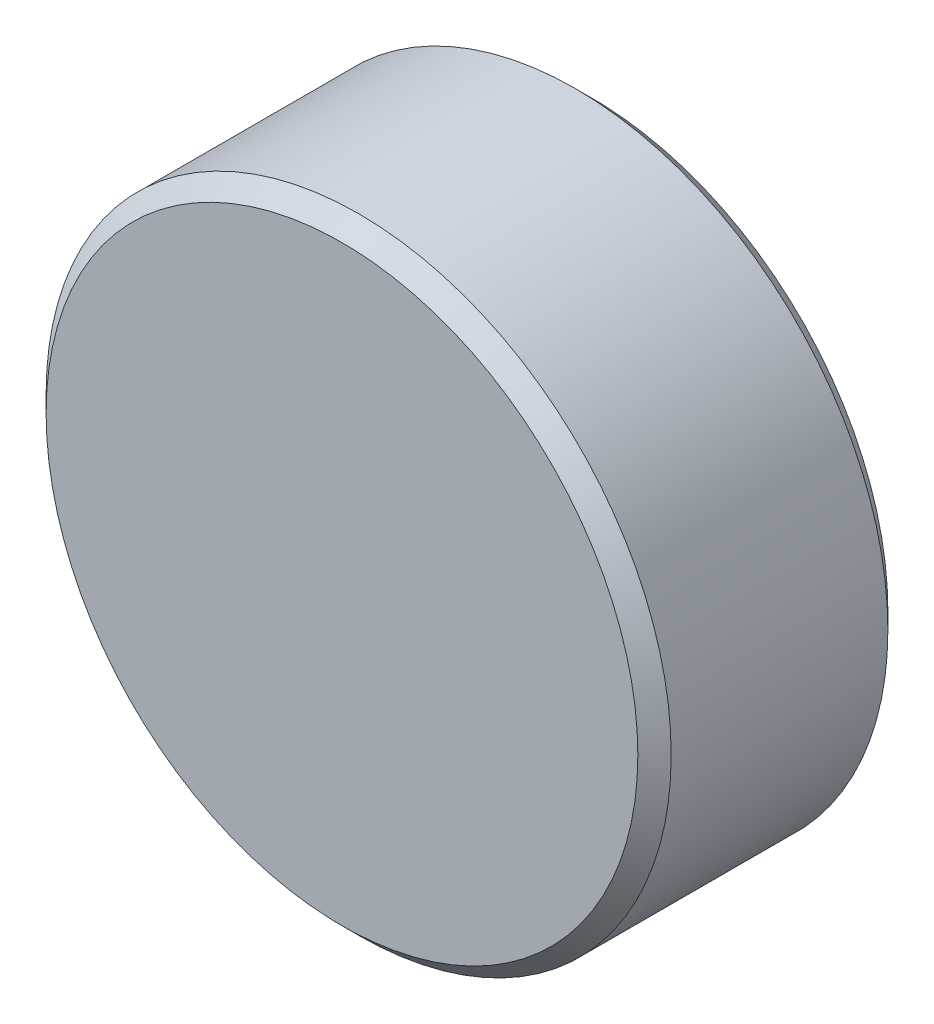
SolidWorks part; units mm, degrees
ref_plane "正面" through (0, 0, 0) normal (0, 0, 1) x (1, 0, 0)
ref_plane "平面" through (0, 0, 0) normal (0, 1, 0) x (1, 0, 0)
ref_plane "右側面" through (0, 0, 0) normal (1, 0, 0) x (0, 0, -1)
sketch "ｽｹｯﾁ1" plane through (0, 0, 0) normal (0, 0, 1) x (1, 0, 0)
  circle A0 centre (0, 0) radius 37.5
  dimension "D1" = 75
extrude "ﾎﾞｽ - 押し出し1" add sketch "ｽｹｯﾁ1" along normal blind 30
chamfer "面取り1" distance 2 angle 45 2 edges at (37.5, 0, 30) (37.5, 0, 0)
